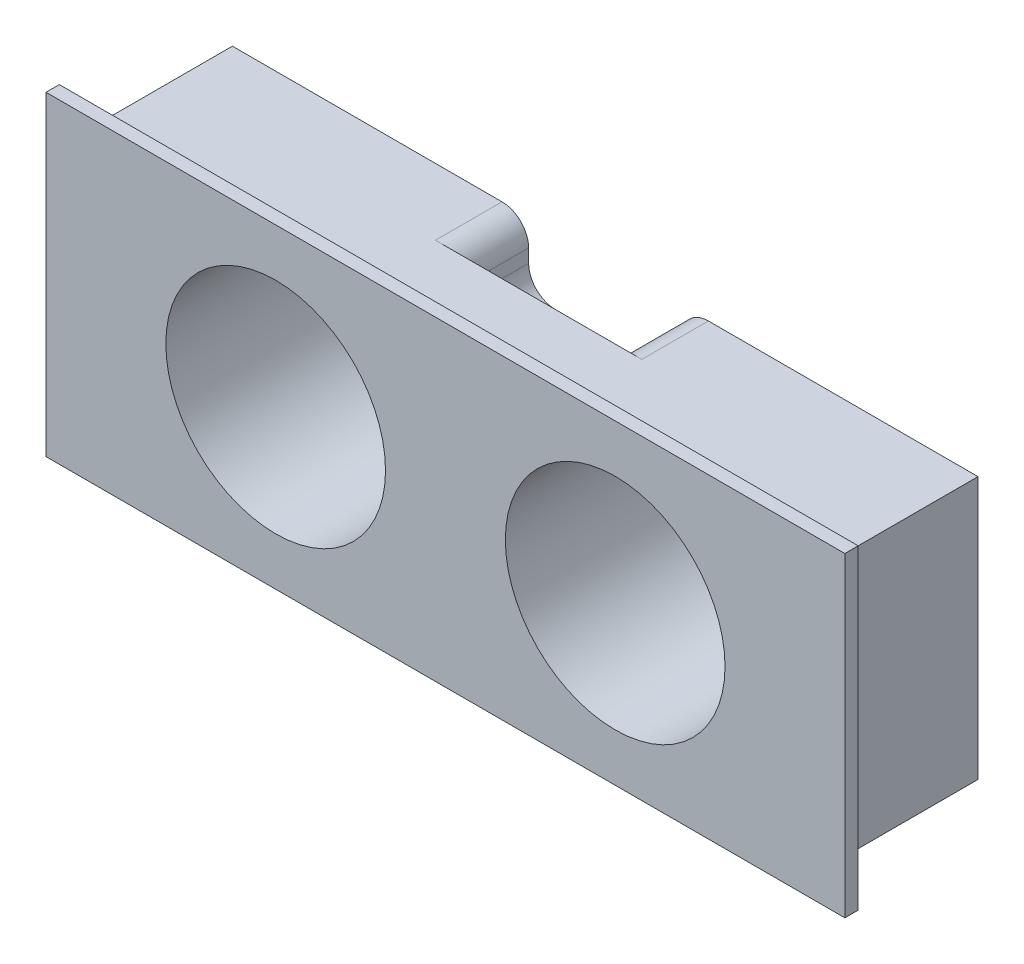
SolidWorks part; units mm, degrees
ref_plane "Front Plane" through (0, 0, 0) normal (0, 0, 1) x (1, 0, 0)
ref_plane "Top Plane" through (0, 0, 0) normal (0, 1, 0) x (1, 0, 0)
ref_plane "Right Plane" through (0, 0, 0) normal (1, 0, 0) x (0, 0, -1)
sketch "Sketch1" plane through (0, 0, 0) normal (0, 0, 1) x (1, 0, 0)
  line L0 (28, -9.85) -> (-28, 9.85) construction
  line L1 (-28, 9.85) -> (28, 9.85)
  line L2 (-28, 9.85) -> (-28, -9.85)
  line L3 (-28, -9.85) -> (28, -9.85)
  line L4 (28, 9.85) -> (28, -9.85)
  line L5 (28, 9.85) -> (-28, -9.85) construction
  point P4 (0, 0)
  dimension "D5" = 19.7
  dimension "D6" = 56
extrude "Boss-Extrude2" add sketch "Sketch1" along normal blind 11
sketch "Sketch3" plane through (0, 0, 11) normal (0, 0, 1) x (1, 0, 0)
  line L0 (-28, 9.85) -> (-28, -9.85) construction
  line L1 (-30, 11.85) -> (30, 11.85)
  line L2 (-30, 11.85) -> (-30, -11.85)
  line L3 (-30, -11.85) -> (30, -11.85)
  line L4 (30, 11.85) -> (30, -11.85)
  line L5 (28, -9.85) -> (28, 9.85) construction
  line L6 (28, 9.85) -> (-28, 9.85) construction
  line L7 (-28, -9.85) -> (28, -9.85) construction
  dimension "D1" = 2
  dimension "D2" = 2
  dimension "D3" = 2
  dimension "D4" = 2
extrude "Boss-Extrude3" add sketch "Sketch3" along normal blind 1
sketch "Sketch4" plane through (0, 0, 12) normal (0, 0, 1) x (1, 0, 0)
  line L1 (12.75, 0) -> (-12.75, 0) construction
  circle A0 centre (-12.75, 0) radius 8.25
  circle A1 centre (12.75, 0) radius 8.25
  point P9 (0, 0)
  dimension "D1" = 16.5
  dimension "D3" = 25.5
extrude "Cut-Extrude1" cut sketch "Sketch4" against normal through all
sketch "Sketch5" plane through (0, 0, 0) normal (0, 0, -1) x (-1, 0, 0)
  line L0 (-28, 9.85) -> (28, 9.85) construction
  line L1 (-5.75, 9.85) -> (5.75, 9.85)
  line L2 (-5.75, 9.85) -> (-5.75, 6.85)
  line L3 (-3.75, 4.85) -> (3.75, 4.85)
  line L4 (5.75, 9.85) -> (5.75, 6.85)
  arc A0 (3.75, 4.85) -> (5.75, 6.85) centre (3.75, 6.85) ccw
  arc A1 (-5.75, 6.85) -> (-3.75, 4.85) centre (-3.75, 6.85) ccw
  point P2 (0, 4.85)
  point P9 (5.75, 4.85)
  dimension "D3" = 2
  dimension "D1" = 5
  dimension "D2" = 11.5
extrude "Cut-Extrude2" cut sketch "Sketch5" against normal blind 5
fillet "Fillet1" radius 2 2 edges at (-5.75, 9.85, 2.5) (5.75, 9.85, 2.5)
sketch "Sketch6" plane through (0, 0, 0) normal (0, 0, -1) x (-1, 0, 0)
  line L0 (28, -9.85) -> (-28, -9.85) construction
  line L1 (-3.75, -4.85) -> (3.75, -4.85)
  line L2 (-5.75, -6.85) -> (-5.75, -9.85)
  line L3 (-5.75, -9.85) -> (5.75, -9.85)
  line L4 (5.75, -6.85) -> (5.75, -9.85)
  line L5 (5.75, 6.85) -> (5.75, 7.85) construction
  line L6 (-5.75, 7.85) -> (-5.75, 6.85) construction
  arc A0 (3.75, -4.85) -> (5.75, -6.85) centre (3.75, -6.85) cw
  arc A1 (-3.75, -4.85) -> (-5.75, -6.85) centre (-3.75, -6.85) ccw
  point P6 (0, -9.85)
  point P8 (5.75, 7.35)
  point P11 (-5.75, 7.35)
  point P16 (5.75, -4.85)
  point P19 (-5.75, -4.85)
  dimension "D3" = 2
  dimension "D1" = 11.5
  dimension "D2" = 5
extrude "Cut-Extrude3" cut sketch "Sketch6" against normal blind 5
fillet "Fillet2" radius 2 2 edges at (-5.75, -9.85, 2.5) (5.75, -9.85, 2.5)
sketch "Sketch8" plane through (0, 9.85, 0) normal (0, 1, 0) x (1, 0, 0)
  line L0 (28, -11) -> (-28, -11) construction
  line L1 (26, -11) -> (22, -11)
  line L2 (26, -11) -> (26, -3)
  line L3 (26, -3) -> (22, -3)
  line L4 (22, -11) -> (22, -3)
  line L5 (28, -11) -> (28, 0) construction
  line L6 (-22, -11) -> (-26, -11)
  line L7 (-22, -11) -> (-22, -3)
  line L8 (-22, -3) -> (-26, -3)
  line L9 (-26, -11) -> (-26, -3)
  line L10 (-28, -11) -> (-28, 0) construction
  dimension "D1" = 2
  dimension "D2" = 2
  dimension "D3" = 4
  dimension "D4" = 4
  dimension "D5" = 8
  dimension "D6" = 8
extrude "Cut-Extrude4" [suppressed] cut sketch "Sketch8" against normal blind 2
sketch "Sketch9" plane through (0, -9.85, 0) normal (0, -1, 0) x (1, 0, 0)
  line L0 (-28, 11) -> (28, 11) construction
  line L1 (26, 11) -> (22, 11)
  line L2 (26, 11) -> (26, 3)
  line L3 (26, 3) -> (22, 3)
  line L4 (22, 11) -> (22, 3)
  line L6 (-22, 11) -> (-26, 11)
  line L7 (-22, 11) -> (-22, 3)
  line L8 (-22, 3) -> (-26, 3)
  line L9 (-26, 11) -> (-26, 3)
  line L11 (28, 11) -> (28, 0) construction
  line L12 (-28, 11) -> (-28, 0) construction
  dimension "D1" = 2
  dimension "D2" = 4
  dimension "D3" = 8
  dimension "D4" = 2
  dimension "D5" = 4
  dimension "D6" = 8
extrude "Cut-Extrude5" [suppressed] cut sketch "Sketch9" against normal blind 2
equation "\"ˇ11.00mm\"=7"
